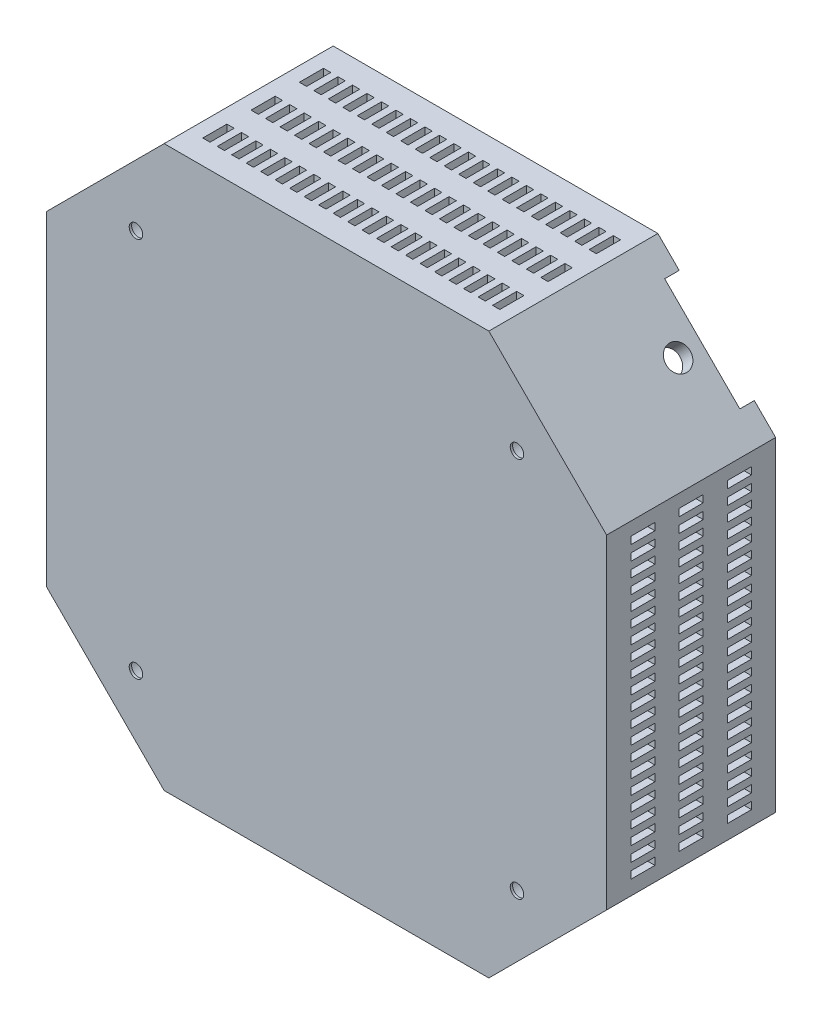
SolidWorks part; units mm, degrees
ref_plane "Plan de face" through (0, 0, 0) normal (0, 0, 1) x (1, 0, 0)
ref_plane "Plan de dessus" through (0, 0, 0) normal (0, 1, 0) x (1, 0, 0)
ref_plane "Plan de droite" through (0, 0, 0) normal (1, 0, 0) x (0, 0, -1)
sketch "Esquisse1" plane through (0, 0, -27.5) normal (0, 0, -1) x (-1, 0, 0)
  line L0 (-2.5656, -55.7278) -> (62.1796, -55.7278) construction
  line L1 (-25.193, -33.1003) -> (-2.5656, -55.7278) construction
  line L2 (-25.193, -33.1003) -> (-25.193, 31.6448) construction
  line L3 (-25.193, 31.6448) -> (-2.5656, 54.2722) construction
  line L4 (84.807, 31.6448) -> (62.1796, 54.2722) construction
  line L5 (-2.5656, 54.2722) -> (62.1796, 54.2722) construction
  line L6 (84.807, -33.1003) -> (84.807, 31.6448) construction
  line L7 (84.807, -33.1003) -> (62.1796, -55.7278) construction
  line L8 (-2.5656, -55.7278) -> (62.1796, -55.7278)
  line L9 (-25.193, -33.1003) -> (-2.5656, -55.7278)
  line L10 (-25.193, -33.1003) -> (-25.193, 31.6448)
  line L11 (-25.193, 31.6448) -> (-2.5656, 54.2722)
  line L12 (84.807, 31.6448) -> (62.1796, 54.2722)
  line L13 (-2.5656, 54.2722) -> (62.1796, 54.2722)
  line L14 (84.807, -33.1003) -> (84.807, 31.6448)
  line L15 (84.807, -33.1003) -> (62.1796, -55.7278)
  circle A0 centre (-9.6366, 38.7159) radius 1.4 construction
  circle A1 centre (69.2507, 38.7159) radius 1.4 construction
  circle A2 centre (69.2507, -40.1714) radius 1.4 construction
  circle A3 centre (-9.6366, -40.1714) radius 1.4 construction
  circle A4 centre (-9.6366, 38.7159) radius 1.4
  circle A5 centre (69.2507, 38.7159) radius 1.4
  circle A6 centre (69.2507, -40.1714) radius 1.4
  circle A7 centre (-9.6366, -40.1714) radius 1.4
extrude "Boss.-Extru.1" add sketch "Esquisse1" along normal blind 3.5
sketch "Esquisse2" plane through (0, 0, -31) normal (0, 0, -1) x (-1, 0, 0)
  circle A0 centre (69.2507, 38.7159) radius 3.25
  dimension "D1" = 6.5
extrude "Enlèv. mat.-Extru.1" cut sketch "Esquisse2" against normal blind 3
ref_plane "Plan2" through (0, -0.7278, 0) normal (0, -1, 0) x (-1, 0, 0)
ref_plane "Plan3" through (-29.807, 0, 0) normal (1, 0, 0) x (0, 0, -1)
mirror "Symétrie3" about plane through (-29.807, 0, 0) normal (1, 0, 0) of "Enlèv. mat.-Extru.1" second plane through (0, -0.7278, 0) second plane normal (0, -1, 0)
sketch "Esquisse12" plane through (0, 0, -27.5) normal (0, 0, 1) x (1, 0, 0)
  line L0 (-87.807, 32.8875) -> (-63.4222, 57.2722)
  line L1 (-63.4222, 57.2722) -> (3.8082, 57.2722)
  line L2 (3.8082, 57.2722) -> (28.193, 32.8875)
  line L3 (28.193, 32.8875) -> (28.193, -34.343)
  line L4 (28.193, -34.343) -> (3.8082, -58.7278)
  line L5 (3.8082, -58.7278) -> (-63.4222, -58.7278)
  line L6 (-63.4222, -58.7278) -> (-87.807, -34.343)
  line L7 (-87.807, -34.343) -> (-87.807, 32.8875)
  line L8 (-84.807, 31.6448) -> (-62.1796, 54.2722) construction
  line L9 (-62.1796, 54.2722) -> (2.5656, 54.2722) construction
  line L10 (2.5656, 54.2722) -> (25.193, 31.6448) construction
  line L11 (25.193, 31.6448) -> (25.193, -33.1003) construction
  line L12 (25.193, -33.1003) -> (2.5656, -55.7278) construction
  line L13 (2.5656, -55.7278) -> (-62.1796, -55.7278) construction
  line L14 (-62.1796, -55.7278) -> (-84.807, -33.1003) construction
  line L15 (-84.807, -33.1003) -> (-84.807, 31.6448) construction
  line L32 (2.5656, -55.7278) -> (25.193, -33.1003)
  line L33 (25.193, -33.1003) -> (25.193, 31.6448)
  line L34 (25.193, 31.6448) -> (2.5656, 54.2722)
  line L35 (2.5656, 54.2722) -> (-62.1796, 54.2722)
  line L36 (-62.1796, 54.2722) -> (-84.807, 31.6448)
  line L37 (-84.807, 31.6448) -> (-84.807, -33.1003)
  line L38 (-84.807, -33.1003) -> (-62.1796, -55.7278)
  line L39 (-62.1796, -55.7278) -> (2.5656, -55.7278)
  line L40 (2.5656, -55.7278) -> (25.193, -33.1003)
  line L41 (25.193, -33.1003) -> (25.193, 31.6448)
  line L42 (25.193, 31.6448) -> (2.5656, 54.2722)
  line L43 (2.5656, 54.2722) -> (-62.1796, 54.2722)
  line L44 (-62.1796, 54.2722) -> (-84.807, 31.6448)
  line L45 (-84.807, 31.6448) -> (-84.807, -33.1003)
  line L46 (-84.807, -33.1003) -> (-62.1796, -55.7278)
  line L47 (-62.1796, -55.7278) -> (2.5656, -55.7278)
  dimension "D1" = 3
  dimension "D2" = 3
  dimension "D3" = 3
  dimension "D4" = 3
  dimension "D5" = 3
  dimension "D6" = 3
  dimension "D7" = 3
  dimension "D8" = 3
  dimension "D9" = 0
extrude "Boss.-Extru.2" add sketch "Esquisse12" along direction (0, 0, 1) on the side against the normal blind 35
sketch "Esquisse13" plane through (0, 0, -62.5) normal (0, 0, -1) x (-1, 0, 0)
  line L0 (-23.7788, 37.3017) -> (-21.6574, 35.1804)
  line L1 (-28.193, 32.8875) -> (-3.8082, 57.2722) construction
  line L2 (-25.193, 31.6448) -> (-2.5656, 54.2722) construction
  line L3 (-21.6574, 35.1804) -> (-6.1011, 50.7367)
  line L4 (-6.1011, 50.7367) -> (-8.2224, 52.858)
  line L5 (-8.2224, 52.858) -> (-23.7788, 37.3017)
  line L6 (29.807, 55) -> (29.807, -55) construction
  line L7 (83.3928, 37.3017) -> (81.2715, 35.1804)
  line L8 (65.7151, 50.7367) -> (67.8365, 52.858)
  line L9 (67.8365, 52.858) -> (83.3928, 37.3017)
  line L10 (81.2715, 35.1804) -> (65.7151, 50.7367)
  line L11 (-55, -0.7278) -> (55, -0.7278) construction
  line L12 (81.2715, -36.6359) -> (65.7151, -52.1922)
  line L13 (67.8365, -54.3135) -> (83.3928, -38.7572)
  line L14 (65.7151, -52.1922) -> (67.8365, -54.3135)
  line L15 (83.3928, -38.7572) -> (81.2715, -36.6359)
  line L16 (-6.1011, -52.1922) -> (-8.2224, -54.3135)
  line L17 (-21.6574, -36.6359) -> (-6.1011, -52.1922)
  line L18 (-23.7788, -38.7572) -> (-21.6574, -36.6359)
  line L19 (-8.2224, -54.3135) -> (-23.7788, -38.7572)
  dimension "D1" = 5
  dimension "D2" = 5
extrude "Enlèv. mat.-Extru.3" cut sketch "Esquisse13" against normal blind 3
sketch "Esquisse15" plane through (30.5402, 30.5402, 0) normal (0.7071, 0.7071, 0) x (0, 0, -1)
  line L0 (27.5, 20.5621) -> (59.5, 20.5621) construction
  line L1 (27.5, 3.3195) -> (27.5, 37.8048) construction
  line L2 (59.5, 31.5621) -> (59.5, 9.5621) construction
  circle A0 centre (54.5, 20.5621) radius 2.5
  dimension "D1" = 5
  dimension "D2" = 5
extrude "Enlèv. mat.-Extru.4" cut sketch "Esquisse15" against normal through all
sketch "Esquisse16" plane through (0, -58.7278, 0) normal (0, -1, 0) x (1, 0, 0)
  line L0 (-63.4222, -27.5) -> (3.8082, -27.5) construction
  line L1 (-60.4222, -32.5) -> (-58.9222, -32.5)
  line L2 (-60.4222, -32.5) -> (-60.4222, -37.5)
  line L3 (-60.4222, -37.5) -> (-58.9222, -37.5)
  line L4 (-58.9222, -32.5) -> (-58.9222, -37.5)
  line L5 (-63.4222, -62.5) -> (-63.4222, -27.5) construction
  line L6 (-57.4222, -32.5) -> (-57.4222, -37.5)
  line L7 (-57.4222, -32.5) -> (-55.9222, -32.5)
  line L8 (-55.9222, -32.5) -> (-55.9222, -37.5)
  line L9 (-57.4222, -37.5) -> (-55.9222, -37.5)
  line L10 (-54.4222, -32.5) -> (-54.4222, -37.5)
  line L11 (-54.4222, -32.5) -> (-52.9222, -32.5)
  line L12 (-52.9222, -32.5) -> (-52.9222, -37.5)
  line L13 (-54.4222, -37.5) -> (-52.9222, -37.5)
  line L14 (-51.4222, -32.5) -> (-51.4222, -37.5)
  line L15 (-51.4222, -32.5) -> (-49.9222, -32.5)
  line L16 (-49.9222, -32.5) -> (-49.9222, -37.5)
  line L17 (-51.4222, -37.5) -> (-49.9222, -37.5)
  line L18 (-48.4222, -32.5) -> (-48.4222, -37.5)
  line L19 (-48.4222, -32.5) -> (-46.9222, -32.5)
  line L20 (-46.9222, -32.5) -> (-46.9222, -37.5)
  line L21 (-48.4222, -37.5) -> (-46.9222, -37.5)
  line L22 (-45.4222, -32.5) -> (-45.4222, -37.5)
  line L23 (-45.4222, -32.5) -> (-43.9222, -32.5)
  line L24 (-43.9222, -32.5) -> (-43.9222, -37.5)
  line L25 (-45.4222, -37.5) -> (-43.9222, -37.5)
  line L26 (-42.4222, -32.5) -> (-42.4222, -37.5)
  line L27 (-42.4222, -32.5) -> (-40.9222, -32.5)
  line L28 (-40.9222, -32.5) -> (-40.9222, -37.5)
  line L29 (-42.4222, -37.5) -> (-40.9222, -37.5)
  line L30 (-39.4222, -32.5) -> (-39.4222, -37.5)
  line L31 (-39.4222, -32.5) -> (-37.9222, -32.5)
  line L32 (-37.9222, -32.5) -> (-37.9222, -37.5)
  line L33 (-39.4222, -37.5) -> (-37.9222, -37.5)
  line L34 (-36.4222, -32.5) -> (-36.4222, -37.5)
  line L35 (-36.4222, -32.5) -> (-34.9222, -32.5)
  line L36 (-34.9222, -32.5) -> (-34.9222, -37.5)
  line L37 (-36.4222, -37.5) -> (-34.9222, -37.5)
  line L38 (-33.4222, -32.5) -> (-33.4222, -37.5)
  line L39 (-33.4222, -32.5) -> (-31.9222, -32.5)
  line L40 (-31.9222, -32.5) -> (-31.9222, -37.5)
  line L41 (-33.4222, -37.5) -> (-31.9222, -37.5)
  line L42 (-30.4222, -32.5) -> (-30.4222, -37.5)
  line L43 (-30.4222, -32.5) -> (-28.9222, -32.5)
  line L44 (-28.9222, -32.5) -> (-28.9222, -37.5)
  line L45 (-30.4222, -37.5) -> (-28.9222, -37.5)
  line L46 (-27.4222, -32.5) -> (-27.4222, -37.5)
  line L47 (-27.4222, -32.5) -> (-25.9222, -32.5)
  line L48 (-25.9222, -32.5) -> (-25.9222, -37.5)
  line L49 (-27.4222, -37.5) -> (-25.9222, -37.5)
  line L50 (-24.4222, -32.5) -> (-24.4222, -37.5)
  line L51 (-24.4222, -32.5) -> (-22.9222, -32.5)
  line L52 (-22.9222, -32.5) -> (-22.9222, -37.5)
  line L53 (-24.4222, -37.5) -> (-22.9222, -37.5)
  line L54 (-21.4222, -32.5) -> (-21.4222, -37.5)
  line L55 (-21.4222, -32.5) -> (-19.9222, -32.5)
  line L56 (-19.9222, -32.5) -> (-19.9222, -37.5)
  line L57 (-21.4222, -37.5) -> (-19.9222, -37.5)
  line L58 (-18.4222, -32.5) -> (-18.4222, -37.5)
  line L59 (-18.4222, -32.5) -> (-16.9222, -32.5)
  line L60 (-16.9222, -32.5) -> (-16.9222, -37.5)
  line L61 (-18.4222, -37.5) -> (-16.9222, -37.5)
  line L62 (-15.4222, -32.5) -> (-15.4222, -37.5)
  line L63 (-15.4222, -32.5) -> (-13.9222, -32.5)
  line L64 (-13.9222, -32.5) -> (-13.9222, -37.5)
  line L65 (-15.4222, -37.5) -> (-13.9222, -37.5)
  line L66 (-12.4222, -32.5) -> (-12.4222, -37.5)
  line L67 (-12.4222, -32.5) -> (-10.9222, -32.5)
  line L68 (-10.9222, -32.5) -> (-10.9222, -37.5)
  line L69 (-12.4222, -37.5) -> (-10.9222, -37.5)
  line L70 (-9.4222, -32.5) -> (-9.4222, -37.5)
  line L71 (-9.4222, -32.5) -> (-7.9222, -32.5)
  line L72 (-7.9222, -32.5) -> (-7.9222, -37.5)
  line L73 (-9.4222, -37.5) -> (-7.9222, -37.5)
  line L74 (-6.4222, -32.5) -> (-6.4222, -37.5)
  line L75 (-6.4222, -32.5) -> (-4.9222, -32.5)
  line L76 (-4.9222, -32.5) -> (-4.9222, -37.5)
  line L77 (-6.4222, -37.5) -> (-4.9222, -37.5)
  line L78 (-3.4222, -32.5) -> (-3.4222, -37.5)
  line L79 (-3.4222, -32.5) -> (-1.9222, -32.5)
  line L80 (-1.9222, -32.5) -> (-1.9222, -37.5)
  line L81 (-3.4222, -37.5) -> (-1.9222, -37.5)
  line L82 (-0.4222, -32.5) -> (-0.4222, -37.5)
  line L83 (-0.4222, -32.5) -> (1.0778, -32.5)
  line L84 (1.0778, -32.5) -> (1.0778, -37.5)
  line L85 (-0.4222, -37.5) -> (1.0778, -37.5)
  line L86 (-57.4222, -42.5) -> (-57.4222, -47.5)
  line L87 (-57.4222, -42.5) -> (-55.9222, -42.5)
  line L88 (-55.9222, -42.5) -> (-55.9222, -47.5)
  line L89 (-57.4222, -47.5) -> (-55.9222, -47.5)
  line L90 (-54.4222, -42.5) -> (-54.4222, -47.5)
  line L91 (-54.4222, -42.5) -> (-52.9222, -42.5)
  line L92 (-52.9222, -42.5) -> (-52.9222, -47.5)
  line L93 (-54.4222, -47.5) -> (-52.9222, -47.5)
  line L94 (-51.4222, -42.5) -> (-51.4222, -47.5)
  line L95 (-51.4222, -42.5) -> (-49.9222, -42.5)
  line L96 (-49.9222, -42.5) -> (-49.9222, -47.5)
  line L97 (-51.4222, -47.5) -> (-49.9222, -47.5)
  line L98 (-48.4222, -42.5) -> (-48.4222, -47.5)
  line L99 (-48.4222, -42.5) -> (-46.9222, -42.5)
  line L100 (-46.9222, -42.5) -> (-46.9222, -47.5)
  line L101 (-48.4222, -47.5) -> (-46.9222, -47.5)
  line L102 (-45.4222, -42.5) -> (-45.4222, -47.5)
  line L103 (-45.4222, -42.5) -> (-43.9222, -42.5)
  line L104 (-43.9222, -42.5) -> (-43.9222, -47.5)
  line L105 (-45.4222, -47.5) -> (-43.9222, -47.5)
  line L106 (-42.4222, -42.5) -> (-42.4222, -47.5)
  line L107 (-42.4222, -42.5) -> (-40.9222, -42.5)
  line L108 (-40.9222, -42.5) -> (-40.9222, -47.5)
  line L109 (-42.4222, -47.5) -> (-40.9222, -47.5)
  line L110 (-39.4222, -42.5) -> (-39.4222, -47.5)
  line L111 (-39.4222, -42.5) -> (-37.9222, -42.5)
  line L112 (-37.9222, -42.5) -> (-37.9222, -47.5)
  line L113 (-39.4222, -47.5) -> (-37.9222, -47.5)
  line L114 (-36.4222, -42.5) -> (-36.4222, -47.5)
  line L115 (-36.4222, -42.5) -> (-34.9222, -42.5)
  line L116 (-34.9222, -42.5) -> (-34.9222, -47.5)
  line L117 (-36.4222, -47.5) -> (-34.9222, -47.5)
  line L118 (-33.4222, -42.5) -> (-33.4222, -47.5)
  line L119 (-33.4222, -42.5) -> (-31.9222, -42.5)
  line L120 (-31.9222, -42.5) -> (-31.9222, -47.5)
  line L121 (-33.4222, -47.5) -> (-31.9222, -47.5)
  line L122 (-30.4222, -42.5) -> (-30.4222, -47.5)
  line L123 (-30.4222, -42.5) -> (-28.9222, -42.5)
  line L124 (-28.9222, -42.5) -> (-28.9222, -47.5)
  line L125 (-30.4222, -47.5) -> (-28.9222, -47.5)
  line L126 (-27.4222, -42.5) -> (-27.4222, -47.5)
  line L127 (-27.4222, -42.5) -> (-25.9222, -42.5)
  line L128 (-25.9222, -42.5) -> (-25.9222, -47.5)
  line L129 (-27.4222, -47.5) -> (-25.9222, -47.5)
  line L130 (-24.4222, -42.5) -> (-24.4222, -47.5)
  line L131 (-24.4222, -42.5) -> (-22.9222, -42.5)
  line L132 (-22.9222, -42.5) -> (-22.9222, -47.5)
  line L133 (-24.4222, -47.5) -> (-22.9222, -47.5)
  line L134 (-21.4222, -42.5) -> (-21.4222, -47.5)
  line L135 (-21.4222, -42.5) -> (-19.9222, -42.5)
  line L136 (-19.9222, -42.5) -> (-19.9222, -47.5)
  line L137 (-21.4222, -47.5) -> (-19.9222, -47.5)
  line L138 (-18.4222, -42.5) -> (-18.4222, -47.5)
  line L139 (-18.4222, -42.5) -> (-16.9222, -42.5)
  line L140 (-16.9222, -42.5) -> (-16.9222, -47.5)
  line L141 (-18.4222, -47.5) -> (-16.9222, -47.5)
  line L142 (-15.4222, -42.5) -> (-15.4222, -47.5)
  line L143 (-15.4222, -42.5) -> (-13.9222, -42.5)
  line L144 (-13.9222, -42.5) -> (-13.9222, -47.5)
  line L145 (-15.4222, -47.5) -> (-13.9222, -47.5)
  line L146 (-12.4222, -42.5) -> (-12.4222, -47.5)
  line L147 (-12.4222, -42.5) -> (-10.9222, -42.5)
  line L148 (-10.9222, -42.5) -> (-10.9222, -47.5)
  line L149 (-12.4222, -47.5) -> (-10.9222, -47.5)
  line L150 (-9.4222, -42.5) -> (-9.4222, -47.5)
  line L151 (-9.4222, -42.5) -> (-7.9222, -42.5)
  line L152 (-7.9222, -42.5) -> (-7.9222, -47.5)
  line L153 (-9.4222, -47.5) -> (-7.9222, -47.5)
  line L154 (-6.4222, -42.5) -> (-6.4222, -47.5)
  line L155 (-6.4222, -42.5) -> (-4.9222, -42.5)
  line L156 (-4.9222, -42.5) -> (-4.9222, -47.5)
  line L157 (-6.4222, -47.5) -> (-4.9222, -47.5)
  line L158 (-3.4222, -42.5) -> (-3.4222, -47.5)
  line L159 (-3.4222, -42.5) -> (-1.9222, -42.5)
  line L160 (-1.9222, -42.5) -> (-1.9222, -47.5)
  line L161 (-3.4222, -47.5) -> (-1.9222, -47.5)
  line L162 (-0.4222, -42.5) -> (-0.4222, -47.5)
  line L163 (-0.4222, -42.5) -> (1.0778, -42.5)
  line L164 (1.0778, -42.5) -> (1.0778, -47.5)
  line L165 (-0.4222, -47.5) -> (1.0778, -47.5)
  line L166 (-57.4222, -52.5) -> (-57.4222, -57.5)
  line L167 (-57.4222, -52.5) -> (-55.9222, -52.5)
  line L168 (-55.9222, -52.5) -> (-55.9222, -57.5)
  line L169 (-57.4222, -57.5) -> (-55.9222, -57.5)
  line L170 (-54.4222, -52.5) -> (-54.4222, -57.5)
  line L171 (-54.4222, -52.5) -> (-52.9222, -52.5)
  line L172 (-52.9222, -52.5) -> (-52.9222, -57.5)
  line L173 (-54.4222, -57.5) -> (-52.9222, -57.5)
  line L174 (-51.4222, -52.5) -> (-51.4222, -57.5)
  line L175 (-51.4222, -52.5) -> (-49.9222, -52.5)
  line L176 (-49.9222, -52.5) -> (-49.9222, -57.5)
  line L177 (-51.4222, -57.5) -> (-49.9222, -57.5)
  line L178 (-48.4222, -52.5) -> (-48.4222, -57.5)
  line L179 (-48.4222, -52.5) -> (-46.9222, -52.5)
  line L180 (-46.9222, -52.5) -> (-46.9222, -57.5)
  line L181 (-48.4222, -57.5) -> (-46.9222, -57.5)
  line L182 (-45.4222, -52.5) -> (-45.4222, -57.5)
  line L183 (-45.4222, -52.5) -> (-43.9222, -52.5)
  line L184 (-43.9222, -52.5) -> (-43.9222, -57.5)
  line L185 (-45.4222, -57.5) -> (-43.9222, -57.5)
  line L186 (-42.4222, -52.5) -> (-42.4222, -57.5)
  line L187 (-42.4222, -52.5) -> (-40.9222, -52.5)
  line L188 (-40.9222, -52.5) -> (-40.9222, -57.5)
  line L189 (-42.4222, -57.5) -> (-40.9222, -57.5)
  line L190 (-39.4222, -52.5) -> (-39.4222, -57.5)
  line L191 (-39.4222, -52.5) -> (-37.9222, -52.5)
  line L192 (-37.9222, -52.5) -> (-37.9222, -57.5)
  line L193 (-39.4222, -57.5) -> (-37.9222, -57.5)
  line L194 (-36.4222, -52.5) -> (-36.4222, -57.5)
  line L195 (-36.4222, -52.5) -> (-34.9222, -52.5)
  line L196 (-34.9222, -52.5) -> (-34.9222, -57.5)
  line L197 (-36.4222, -57.5) -> (-34.9222, -57.5)
  line L198 (-33.4222, -52.5) -> (-33.4222, -57.5)
  line L199 (-33.4222, -52.5) -> (-31.9222, -52.5)
  line L200 (-31.9222, -52.5) -> (-31.9222, -57.5)
  line L201 (-33.4222, -57.5) -> (-31.9222, -57.5)
  line L202 (-30.4222, -52.5) -> (-30.4222, -57.5)
  line L203 (-30.4222, -52.5) -> (-28.9222, -52.5)
  line L204 (-28.9222, -52.5) -> (-28.9222, -57.5)
  line L205 (-30.4222, -57.5) -> (-28.9222, -57.5)
  line L206 (-27.4222, -52.5) -> (-27.4222, -57.5)
  line L207 (-27.4222, -52.5) -> (-25.9222, -52.5)
  line L208 (-25.9222, -52.5) -> (-25.9222, -57.5)
  line L209 (-27.4222, -57.5) -> (-25.9222, -57.5)
  line L210 (-24.4222, -52.5) -> (-24.4222, -57.5)
  line L211 (-24.4222, -52.5) -> (-22.9222, -52.5)
  line L212 (-22.9222, -52.5) -> (-22.9222, -57.5)
  line L213 (-24.4222, -57.5) -> (-22.9222, -57.5)
  line L214 (-21.4222, -52.5) -> (-21.4222, -57.5)
  line L215 (-21.4222, -52.5) -> (-19.9222, -52.5)
  line L216 (-19.9222, -52.5) -> (-19.9222, -57.5)
  line L217 (-21.4222, -57.5) -> (-19.9222, -57.5)
  line L218 (-18.4222, -52.5) -> (-18.4222, -57.5)
  line L219 (-18.4222, -52.5) -> (-16.9222, -52.5)
  line L220 (-16.9222, -52.5) -> (-16.9222, -57.5)
  line L221 (-18.4222, -57.5) -> (-16.9222, -57.5)
  line L222 (-15.4222, -52.5) -> (-15.4222, -57.5)
  line L223 (-15.4222, -52.5) -> (-13.9222, -52.5)
  line L224 (-13.9222, -52.5) -> (-13.9222, -57.5)
  line L225 (-15.4222, -57.5) -> (-13.9222, -57.5)
  line L226 (-12.4222, -52.5) -> (-12.4222, -57.5)
  line L227 (-12.4222, -52.5) -> (-10.9222, -52.5)
  line L228 (-10.9222, -52.5) -> (-10.9222, -57.5)
  line L229 (-12.4222, -57.5) -> (-10.9222, -57.5)
  line L230 (-9.4222, -52.5) -> (-9.4222, -57.5)
  line L231 (-9.4222, -52.5) -> (-7.9222, -52.5)
  line L232 (-7.9222, -52.5) -> (-7.9222, -57.5)
  line L233 (-9.4222, -57.5) -> (-7.9222, -57.5)
  line L234 (-6.4222, -52.5) -> (-6.4222, -57.5)
  line L235 (-6.4222, -52.5) -> (-4.9222, -52.5)
  line L236 (-4.9222, -52.5) -> (-4.9222, -57.5)
  line L237 (-6.4222, -57.5) -> (-4.9222, -57.5)
  line L238 (-3.4222, -52.5) -> (-3.4222, -57.5)
  line L239 (-3.4222, -52.5) -> (-1.9222, -52.5)
  line L240 (-1.9222, -52.5) -> (-1.9222, -57.5)
  line L241 (-3.4222, -57.5) -> (-1.9222, -57.5)
  line L242 (-0.4222, -52.5) -> (-0.4222, -57.5)
  line L243 (-0.4222, -52.5) -> (1.0778, -52.5)
  line L244 (1.0778, -52.5) -> (1.0778, -57.5)
  line L245 (-0.4222, -57.5) -> (1.0778, -57.5)
  line L246 (-60.4222, -42.5) -> (-60.4222, -47.5)
  line L247 (-60.4222, -42.5) -> (-58.9222, -42.5)
  line L248 (-58.9222, -42.5) -> (-58.9222, -47.5)
  line L249 (-60.4222, -47.5) -> (-58.9222, -47.5)
  line L250 (-60.4222, -52.5) -> (-60.4222, -57.5)
  line L251 (-60.4222, -52.5) -> (-58.9222, -52.5)
  line L252 (-58.9222, -52.5) -> (-58.9222, -57.5)
  line L253 (-60.4222, -57.5) -> (-58.9222, -57.5)
  line L254 (-60.4222, -32.5) -> (-57.4222, -32.5) construction
  line L255 (-60.4222, -32.5) -> (-60.4222, -42.5) construction
  dimension "D1" = 5
  dimension "D2" = 3
  dimension "D3" = 1.5
  dimension "D4" = 5
  dimension "D7" = 3
  dimension "D8" = 10
  dimension "D5" = 21
  dimension "D6" = 3
extrude "Enlèv. mat.-Extru.5" cut sketch "Esquisse16" against normal through all
sketch "Esquisse19" plane through (28.193, 0, 0) normal (1, 0, 0) x (0, 0, -1)
  line L0 (62.5, -34.343) -> (27.5, -34.343) construction
  line L1 (32.5, -29.843) -> (37.5, -29.843)
  line L2 (32.5, -29.843) -> (32.5, -31.343)
  line L3 (32.5, -31.343) -> (37.5, -31.343)
  line L4 (37.5, -29.843) -> (37.5, -31.343)
  line L5 (27.5, -34.343) -> (27.5, 32.8875) construction
  line L6 (42.5, -29.843) -> (42.5, -31.343)
  line L7 (42.5, -29.843) -> (47.5, -29.843)
  line L8 (47.5, -29.843) -> (47.5, -31.343)
  line L9 (42.5, -31.343) -> (47.5, -31.343)
  line L10 (52.5, -29.843) -> (52.5, -31.343)
  line L11 (52.5, -29.843) -> (57.5, -29.843)
  line L12 (57.5, -29.843) -> (57.5, -31.343)
  line L13 (52.5, -31.343) -> (57.5, -31.343)
  line L14 (42.5, -26.843) -> (42.5, -28.343)
  line L15 (42.5, -26.843) -> (47.5, -26.843)
  line L16 (47.5, -26.843) -> (47.5, -28.343)
  line L17 (42.5, -28.343) -> (47.5, -28.343)
  line L18 (52.5, -26.843) -> (52.5, -28.343)
  line L19 (52.5, -26.843) -> (57.5, -26.843)
  line L20 (57.5, -26.843) -> (57.5, -28.343)
  line L21 (52.5, -28.343) -> (57.5, -28.343)
  line L22 (42.5, -23.843) -> (42.5, -25.343)
  line L23 (42.5, -23.843) -> (47.5, -23.843)
  line L24 (47.5, -23.843) -> (47.5, -25.343)
  line L25 (42.5, -25.343) -> (47.5, -25.343)
  line L26 (52.5, -23.843) -> (52.5, -25.343)
  line L27 (52.5, -23.843) -> (57.5, -23.843)
  line L28 (57.5, -23.843) -> (57.5, -25.343)
  line L29 (52.5, -25.343) -> (57.5, -25.343)
  line L30 (42.5, -20.843) -> (42.5, -22.343)
  line L31 (42.5, -20.843) -> (47.5, -20.843)
  line L32 (47.5, -20.843) -> (47.5, -22.343)
  line L33 (42.5, -22.343) -> (47.5, -22.343)
  line L34 (52.5, -20.843) -> (52.5, -22.343)
  line L35 (52.5, -20.843) -> (57.5, -20.843)
  line L36 (57.5, -20.843) -> (57.5, -22.343)
  line L37 (52.5, -22.343) -> (57.5, -22.343)
  line L38 (42.5, -17.843) -> (42.5, -19.343)
  line L39 (42.5, -17.843) -> (47.5, -17.843)
  line L40 (47.5, -17.843) -> (47.5, -19.343)
  line L41 (42.5, -19.343) -> (47.5, -19.343)
  line L42 (52.5, -17.843) -> (52.5, -19.343)
  line L43 (52.5, -17.843) -> (57.5, -17.843)
  line L44 (57.5, -17.843) -> (57.5, -19.343)
  line L45 (52.5, -19.343) -> (57.5, -19.343)
  line L46 (42.5, -14.843) -> (42.5, -16.343)
  line L47 (42.5, -14.843) -> (47.5, -14.843)
  line L48 (47.5, -14.843) -> (47.5, -16.343)
  line L49 (42.5, -16.343) -> (47.5, -16.343)
  line L50 (52.5, -14.843) -> (52.5, -16.343)
  line L51 (52.5, -14.843) -> (57.5, -14.843)
  line L52 (57.5, -14.843) -> (57.5, -16.343)
  line L53 (52.5, -16.343) -> (57.5, -16.343)
  line L54 (42.5, -11.843) -> (42.5, -13.343)
  line L55 (42.5, -11.843) -> (47.5, -11.843)
  line L56 (47.5, -11.843) -> (47.5, -13.343)
  line L57 (42.5, -13.343) -> (47.5, -13.343)
  line L58 (52.5, -11.843) -> (52.5, -13.343)
  line L59 (52.5, -11.843) -> (57.5, -11.843)
  line L60 (57.5, -11.843) -> (57.5, -13.343)
  line L61 (52.5, -13.343) -> (57.5, -13.343)
  line L62 (42.5, -8.843) -> (42.5, -10.343)
  line L63 (42.5, -8.843) -> (47.5, -8.843)
  line L64 (47.5, -8.843) -> (47.5, -10.343)
  line L65 (42.5, -10.343) -> (47.5, -10.343)
  line L66 (52.5, -8.843) -> (52.5, -10.343)
  line L67 (52.5, -8.843) -> (57.5, -8.843)
  line L68 (57.5, -8.843) -> (57.5, -10.343)
  line L69 (52.5, -10.343) -> (57.5, -10.343)
  line L70 (42.5, -5.843) -> (42.5, -7.343)
  line L71 (42.5, -5.843) -> (47.5, -5.843)
  line L72 (47.5, -5.843) -> (47.5, -7.343)
  line L73 (42.5, -7.343) -> (47.5, -7.343)
  line L74 (52.5, -5.843) -> (52.5, -7.343)
  line L75 (52.5, -5.843) -> (57.5, -5.843)
  line L76 (57.5, -5.843) -> (57.5, -7.343)
  line L77 (52.5, -7.343) -> (57.5, -7.343)
  line L78 (42.5, -2.843) -> (42.5, -4.343)
  line L79 (42.5, -2.843) -> (47.5, -2.843)
  line L80 (47.5, -2.843) -> (47.5, -4.343)
  line L81 (42.5, -4.343) -> (47.5, -4.343)
  line L82 (52.5, -2.843) -> (52.5, -4.343)
  line L83 (52.5, -2.843) -> (57.5, -2.843)
  line L84 (57.5, -2.843) -> (57.5, -4.343)
  line L85 (52.5, -4.343) -> (57.5, -4.343)
  line L86 (42.5, 0.157) -> (42.5, -1.343)
  line L87 (42.5, 0.157) -> (47.5, 0.157)
  line L88 (47.5, 0.157) -> (47.5, -1.343)
  line L89 (42.5, -1.343) -> (47.5, -1.343)
  line L90 (52.5, 0.157) -> (52.5, -1.343)
  line L91 (52.5, 0.157) -> (57.5, 0.157)
  line L92 (57.5, 0.157) -> (57.5, -1.343)
  line L93 (52.5, -1.343) -> (57.5, -1.343)
  line L94 (42.5, 3.157) -> (42.5, 1.657)
  line L95 (42.5, 3.157) -> (47.5, 3.157)
  line L96 (47.5, 3.157) -> (47.5, 1.657)
  line L97 (42.5, 1.657) -> (47.5, 1.657)
  line L98 (52.5, 3.157) -> (52.5, 1.657)
  line L99 (52.5, 3.157) -> (57.5, 3.157)
  line L100 (57.5, 3.157) -> (57.5, 1.657)
  line L101 (52.5, 1.657) -> (57.5, 1.657)
  line L102 (42.5, 6.157) -> (42.5, 4.657)
  line L103 (42.5, 6.157) -> (47.5, 6.157)
  line L104 (47.5, 6.157) -> (47.5, 4.657)
  line L105 (42.5, 4.657) -> (47.5, 4.657)
  line L106 (52.5, 6.157) -> (52.5, 4.657)
  line L107 (52.5, 6.157) -> (57.5, 6.157)
  line L108 (57.5, 6.157) -> (57.5, 4.657)
  line L109 (52.5, 4.657) -> (57.5, 4.657)
  line L110 (42.5, 9.157) -> (42.5, 7.657)
  line L111 (42.5, 9.157) -> (47.5, 9.157)
  line L112 (47.5, 9.157) -> (47.5, 7.657)
  line L113 (42.5, 7.657) -> (47.5, 7.657)
  line L114 (52.5, 9.157) -> (52.5, 7.657)
  line L115 (52.5, 9.157) -> (57.5, 9.157)
  line L116 (57.5, 9.157) -> (57.5, 7.657)
  line L117 (52.5, 7.657) -> (57.5, 7.657)
  line L118 (42.5, 12.157) -> (42.5, 10.657)
  line L119 (42.5, 12.157) -> (47.5, 12.157)
  line L120 (47.5, 12.157) -> (47.5, 10.657)
  line L121 (42.5, 10.657) -> (47.5, 10.657)
  line L122 (52.5, 12.157) -> (52.5, 10.657)
  line L123 (52.5, 12.157) -> (57.5, 12.157)
  line L124 (57.5, 12.157) -> (57.5, 10.657)
  line L125 (52.5, 10.657) -> (57.5, 10.657)
  line L126 (42.5, 15.157) -> (42.5, 13.657)
  line L127 (42.5, 15.157) -> (47.5, 15.157)
  line L128 (47.5, 15.157) -> (47.5, 13.657)
  line L129 (42.5, 13.657) -> (47.5, 13.657)
  line L130 (52.5, 15.157) -> (52.5, 13.657)
  line L131 (52.5, 15.157) -> (57.5, 15.157)
  line L132 (57.5, 15.157) -> (57.5, 13.657)
  line L133 (52.5, 13.657) -> (57.5, 13.657)
  line L134 (42.5, 18.157) -> (42.5, 16.657)
  line L135 (42.5, 18.157) -> (47.5, 18.157)
  line L136 (47.5, 18.157) -> (47.5, 16.657)
  line L137 (42.5, 16.657) -> (47.5, 16.657)
  line L138 (52.5, 18.157) -> (52.5, 16.657)
  line L139 (52.5, 18.157) -> (57.5, 18.157)
  line L140 (57.5, 18.157) -> (57.5, 16.657)
  line L141 (52.5, 16.657) -> (57.5, 16.657)
  line L142 (42.5, 21.157) -> (42.5, 19.657)
  line L143 (42.5, 21.157) -> (47.5, 21.157)
  line L144 (47.5, 21.157) -> (47.5, 19.657)
  line L145 (42.5, 19.657) -> (47.5, 19.657)
  line L146 (52.5, 21.157) -> (52.5, 19.657)
  line L147 (52.5, 21.157) -> (57.5, 21.157)
  line L148 (57.5, 21.157) -> (57.5, 19.657)
  line L149 (52.5, 19.657) -> (57.5, 19.657)
  line L150 (42.5, 24.157) -> (42.5, 22.657)
  line L151 (42.5, 24.157) -> (47.5, 24.157)
  line L152 (47.5, 24.157) -> (47.5, 22.657)
  line L153 (42.5, 22.657) -> (47.5, 22.657)
  line L154 (52.5, 24.157) -> (52.5, 22.657)
  line L155 (52.5, 24.157) -> (57.5, 24.157)
  line L156 (57.5, 24.157) -> (57.5, 22.657)
  line L157 (52.5, 22.657) -> (57.5, 22.657)
  line L158 (42.5, 27.157) -> (42.5, 25.657)
  line L159 (42.5, 27.157) -> (47.5, 27.157)
  line L160 (47.5, 27.157) -> (47.5, 25.657)
  line L161 (42.5, 25.657) -> (47.5, 25.657)
  line L162 (52.5, 27.157) -> (52.5, 25.657)
  line L163 (52.5, 27.157) -> (57.5, 27.157)
  line L164 (57.5, 27.157) -> (57.5, 25.657)
  line L165 (52.5, 25.657) -> (57.5, 25.657)
  line L166 (42.5, 30.157) -> (42.5, 28.657)
  line L167 (42.5, 30.157) -> (47.5, 30.157)
  line L168 (47.5, 30.157) -> (47.5, 28.657)
  line L169 (42.5, 28.657) -> (47.5, 28.657)
  line L170 (52.5, 30.157) -> (52.5, 28.657)
  line L171 (52.5, 30.157) -> (57.5, 30.157)
  line L172 (57.5, 30.157) -> (57.5, 28.657)
  line L173 (52.5, 28.657) -> (57.5, 28.657)
  line L174 (32.5, -26.843) -> (32.5, -28.343)
  line L175 (32.5, -26.843) -> (37.5, -26.843)
  line L176 (37.5, -26.843) -> (37.5, -28.343)
  line L177 (32.5, -28.343) -> (37.5, -28.343)
  line L178 (32.5, -23.843) -> (32.5, -25.343)
  line L179 (32.5, -23.843) -> (37.5, -23.843)
  line L180 (37.5, -23.843) -> (37.5, -25.343)
  line L181 (32.5, -25.343) -> (37.5, -25.343)
  line L182 (32.5, -20.843) -> (32.5, -22.343)
  line L183 (32.5, -20.843) -> (37.5, -20.843)
  line L184 (37.5, -20.843) -> (37.5, -22.343)
  line L185 (32.5, -22.343) -> (37.5, -22.343)
  line L186 (32.5, -17.843) -> (32.5, -19.343)
  line L187 (32.5, -17.843) -> (37.5, -17.843)
  line L188 (37.5, -17.843) -> (37.5, -19.343)
  line L189 (32.5, -19.343) -> (37.5, -19.343)
  line L190 (32.5, -14.843) -> (32.5, -16.343)
  line L191 (32.5, -14.843) -> (37.5, -14.843)
  line L192 (37.5, -14.843) -> (37.5, -16.343)
  line L193 (32.5, -16.343) -> (37.5, -16.343)
  line L194 (32.5, -11.843) -> (32.5, -13.343)
  line L195 (32.5, -11.843) -> (37.5, -11.843)
  line L196 (37.5, -11.843) -> (37.5, -13.343)
  line L197 (32.5, -13.343) -> (37.5, -13.343)
  line L198 (32.5, -8.843) -> (32.5, -10.343)
  line L199 (32.5, -8.843) -> (37.5, -8.843)
  line L200 (37.5, -8.843) -> (37.5, -10.343)
  line L201 (32.5, -10.343) -> (37.5, -10.343)
  line L202 (32.5, -5.843) -> (32.5, -7.343)
  line L203 (32.5, -5.843) -> (37.5, -5.843)
  line L204 (37.5, -5.843) -> (37.5, -7.343)
  line L205 (32.5, -7.343) -> (37.5, -7.343)
  line L206 (32.5, -2.843) -> (32.5, -4.343)
  line L207 (32.5, -2.843) -> (37.5, -2.843)
  line L208 (37.5, -2.843) -> (37.5, -4.343)
  line L209 (32.5, -4.343) -> (37.5, -4.343)
  line L210 (32.5, 0.157) -> (32.5, -1.343)
  line L211 (32.5, 0.157) -> (37.5, 0.157)
  line L212 (37.5, 0.157) -> (37.5, -1.343)
  line L213 (32.5, -1.343) -> (37.5, -1.343)
  line L214 (32.5, 3.157) -> (32.5, 1.657)
  line L215 (32.5, 3.157) -> (37.5, 3.157)
  line L216 (37.5, 3.157) -> (37.5, 1.657)
  line L217 (32.5, 1.657) -> (37.5, 1.657)
  line L218 (32.5, 6.157) -> (32.5, 4.657)
  line L219 (32.5, 6.157) -> (37.5, 6.157)
  line L220 (37.5, 6.157) -> (37.5, 4.657)
  line L221 (32.5, 4.657) -> (37.5, 4.657)
  line L222 (32.5, 9.157) -> (32.5, 7.657)
  line L223 (32.5, 9.157) -> (37.5, 9.157)
  line L224 (37.5, 9.157) -> (37.5, 7.657)
  line L225 (32.5, 7.657) -> (37.5, 7.657)
  line L226 (32.5, 12.157) -> (32.5, 10.657)
  line L227 (32.5, 12.157) -> (37.5, 12.157)
  line L228 (37.5, 12.157) -> (37.5, 10.657)
  line L229 (32.5, 10.657) -> (37.5, 10.657)
  line L230 (32.5, 15.157) -> (32.5, 13.657)
  line L231 (32.5, 15.157) -> (37.5, 15.157)
  line L232 (37.5, 15.157) -> (37.5, 13.657)
  line L233 (32.5, 13.657) -> (37.5, 13.657)
  line L234 (32.5, 18.157) -> (32.5, 16.657)
  line L235 (32.5, 18.157) -> (37.5, 18.157)
  line L236 (37.5, 18.157) -> (37.5, 16.657)
  line L237 (32.5, 16.657) -> (37.5, 16.657)
  line L238 (32.5, 21.157) -> (32.5, 19.657)
  line L239 (32.5, 21.157) -> (37.5, 21.157)
  line L240 (37.5, 21.157) -> (37.5, 19.657)
  line L241 (32.5, 19.657) -> (37.5, 19.657)
  line L242 (32.5, 24.157) -> (32.5, 22.657)
  line L243 (32.5, 24.157) -> (37.5, 24.157)
  line L244 (37.5, 24.157) -> (37.5, 22.657)
  line L245 (32.5, 22.657) -> (37.5, 22.657)
  line L246 (32.5, 27.157) -> (32.5, 25.657)
  line L247 (32.5, 27.157) -> (37.5, 27.157)
  line L248 (37.5, 27.157) -> (37.5, 25.657)
  line L249 (32.5, 25.657) -> (37.5, 25.657)
  line L250 (32.5, 30.157) -> (32.5, 28.657)
  line L251 (32.5, 30.157) -> (37.5, 30.157)
  line L252 (37.5, 30.157) -> (37.5, 28.657)
  line L253 (32.5, 28.657) -> (37.5, 28.657)
  line L254 (32.5, -29.843) -> (42.5, -29.843) construction
  line L255 (32.5, -29.843) -> (32.5, -26.843) construction
  dimension "D1" = 5
  dimension "D2" = 3
  dimension "D3" = 5
  dimension "D4" = 1.5
  dimension "D7" = 10
  dimension "D8" = 3
  dimension "D5" = 3
  dimension "D6" = 21
extrude "Enlèv. mat.-Extru.6" cut sketch "Esquisse19" against normal through all
